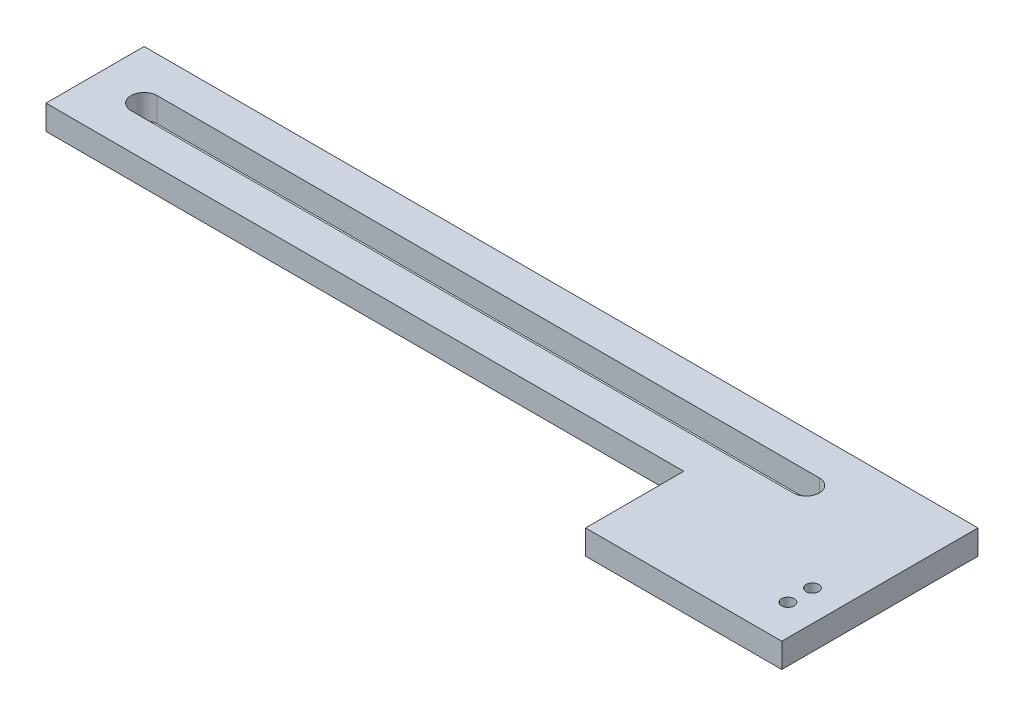
SolidWorks part; units mm, degrees
ref_plane "Front Plane" through (0, 0, 0) normal (0, 0, 1) x (1, 0, 0)
ref_plane "Top Plane" through (0, 0, 0) normal (0, 1, 0) x (1, 0, 0)
ref_plane "Right Plane" through (0, 0, 0) normal (1, 0, 0) x (0, 0, -1)
sketch "Sketch1" plane through (0, 0, 0) normal (0, 1, 0) x (1, 0, 0)
  line L0 (0, 0) -> (215.9, 0)
  line L1 (215.9, 0) -> (215.9, -50.8)
  line L2 (215.9, -50.8) -> (165.1, -50.8)
  line L3 (165.1, -50.8) -> (165.1, -25.4)
  line L4 (165.1, -25.4) -> (0, -25.4)
  line L5 (0, -25.4) -> (0, 0)
  dimension "D1" = 215.9
  dimension "D2" = 25.4
  dimension "D3" = 50.8
  dimension "D4" = 50.8
extrude "Boss-Extrude1" add sketch "Sketch1" along normal blind 6.35
sketch "Sketch2" plane through (0, 6.35, 0) normal (0, 1, 0) x (1, 0, 0)
  line L0 (184.15, -12.7) -> (12.7, -12.7) construction
  line L1 (184.15, -16.0782) -> (12.7, -16.0782)
  line L2 (184.15, -9.3218) -> (12.7, -9.3218)
  line L3 (215.9, -50.8) -> (215.9, 0) construction
  line L4 (215.9, 0) -> (0, 0) construction
  arc A0 (184.15, -16.0782) -> (184.15, -9.3218) centre (184.15, -12.7) ccw
  arc A1 (12.7, -9.3218) -> (12.7, -16.0782) centre (12.7, -12.7) ccw
  point P2 (98.425, -12.7)
  dimension "D1" = 31.75
  dimension "D2" = 12.7
extrude "Cut-Extrude1" cut sketch "Sketch2" against normal through all
hole_wizard "CSK for #4 Flat Head Machine Screw1" positions "Sketch4" profile "Sketch3" countersink size "#4" standard "ANSI Inch" end condition through all
sketch "Sketch4" plane through (0, 0, 0) normal (0, -1, 0) x (-1, 0, 0)
  point P0 (-207.9625, -34.925)
  point P3 (-207.9625, -41.275)
sketch "Sketch3" plane through (207.9625, 0, 34.925) normal (1, 0, 0) x (0, 0, -1)
  line L0 (0, 0) -> (0, 6.35)
  line L1 (0, 6.35) -> (1.6319, 6.35)
  line L2 (1.6319, 6.35) -> (1.6319, 1.4098)
  line L3 (1.6319, 1.4098) -> (2.8575, 0)
  line L5 (2.8575, 0) -> (0, 0)
  line L6 (-1.6319, 1.4098) -> (-2.8575, 0) construction
  line L11 (0, -6.35) -> (0, 107.95) construction
  dimension "Thru Hole Dia." = 3.2639
  dimension "Thru Hole Depth" = 6.35
  dimension "Near C'Sink Dia." = 5.715
  dimension "Near C'Sink Angle" = 82
